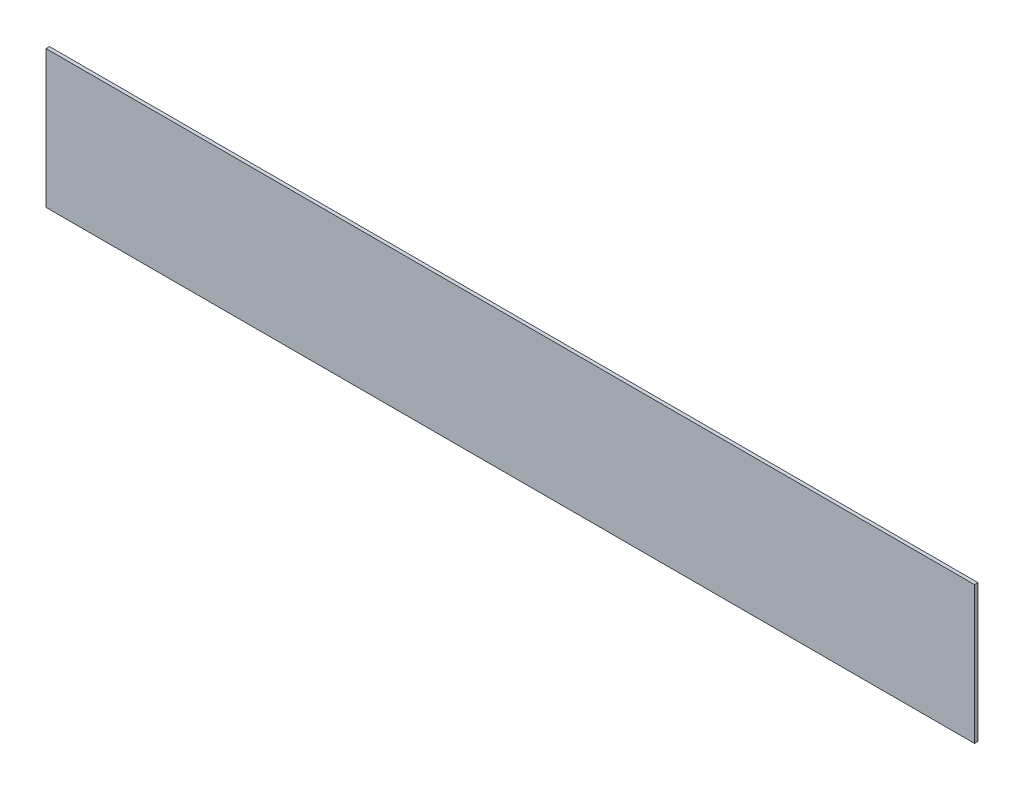
SolidWorks part; units mm, degrees
ref_plane "Plan de face" through (0, 0, 0) normal (0, 0, 1) x (1, 0, 0)
ref_plane "Plan de dessus" through (0, 0, 0) normal (0, 1, 0) x (1, 0, 0)
ref_plane "Plan de droite" through (0, 0, 0) normal (1, 0, 0) x (0, 0, -1)
sketch "Esquisse1" plane through (0, 0, 0) normal (0, 0, 1) x (1, 0, 0)
  line L1 (-135, 20) -> (135, 20)
  line L2 (-135, 20) -> (-135, -20)
  line L3 (-135, -20) -> (135, -20)
  line L4 (135, 20) -> (135, -20)
  line L5 (-135, 20) -> (135, -20) construction
  line L6 (-135, -20) -> (135, 20) construction
  point P0 (0, 0)
  dimension "D1" = 270
  dimension "D2" = 40
extrude "Boss.-Extru.1" add sketch "Esquisse1" along normal blind 1
